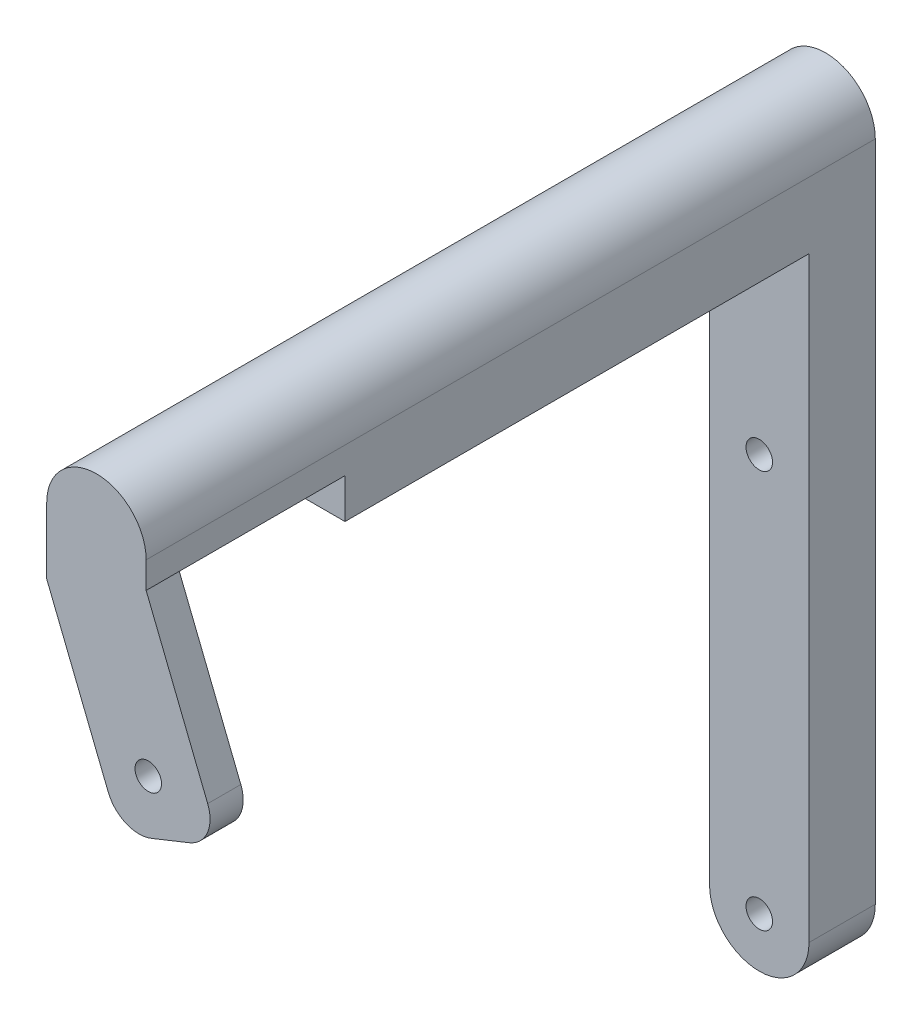
SolidWorks part; units mm, degrees
ref_plane "Plan de face" through (0, 0, 0) normal (0, 0, 1) x (1, 0, 0)
ref_plane "Plan de dessus" through (0, 0, 0) normal (0, 1, 0) x (1, 0, 0)
ref_plane "Plan de droite" through (0, 0, 0) normal (1, 0, 0) x (0, 0, -1)
sketch "Esquisse1" plane through (0, 0, 0) normal (0, 0, 1) x (1, 0, 0)
  line L0 (-15, 0) -> (-15, -200)
  line L1 (15, 0) -> (15, -200)
  circle A0 centre (0, 0) radius 4
  circle A1 centre (0, 0) radius 15
  circle A2 centre (0, -200) radius 15
  circle A4 centre (0, -80) radius 15
  circle A5 centre (0, -80) radius 4
  circle A6 centre (0, -200) radius 4
  dimension "D1" = 8
  dimension "D2" = 30
  dimension "D3" = 200
  dimension "D4" = 80
extrude "Boss.-Extru.1" add sketch "Esquisse1" along normal blind 20 contours A1 A0 | A4 A5 | A4 L1 A1 L0 | A4 L0 A2 L1 | A2 A6
sketch "Esquisse2" plane through (0, 0, 20) normal (0, 0, 1) x (1, 0, 0)
  line L0 (15, 0) -> (15, -200) construction
  line L2 (-15, 0) -> (-15, -20)
  line L3 (-15, -20) -> (15, -20)
  line L4 (15, 0) -> (15, -20)
  arc A0 (15, 0) -> (-15, 0) centre (0, 0) ccw construction
  arc A1 (15, 0) -> (-15, 0) centre (0, 0) ccw
  dimension "D1" = 20
extrude "Boss.-Extru.2" add sketch "Esquisse2" along normal blind 200
sketch "Esquisse5" plane through (0, 0, 220) normal (0, 0, 1) x (1, 0, 0)
  line L0 (-15, -20) -> (15, -8)
  line L1 (15, -20) -> (15, 0) construction
  line L2 (15, -8) -> (15, -20)
  line L3 (-15, -20) -> (15, -20) construction
  line L4 (-15, -20) -> (15, -20)
  dimension "D1" = 12
extrude "Enlèv. mat.-Extru.2" cut sketch "Esquisse5" against normal blind 60
sketch "Esquisse3" plane through (-1.0728, -14.4291, 0) normal (0.3714, -0.9285, 0) x (0.9285, 0.3714, 0)
  line L1 (-15, 220) -> (17.311, 220)
  line L2 (-15, 220) -> (-15, 210)
  line L3 (-15, 210) -> (17.311, 210)
  line L4 (17.311, 220) -> (17.311, 210)
  line L5 (17.311, 160) -> (17.311, 220) construction
  line L6 (17.311, 220) -> (-15, 220) construction
  dimension "D1" = 10
extrude "Boss.-Extru.3" add sketch "Esquisse3" along normal blind 60
fillet "Congé2" radius 10 2 edges at (37.2834, -63.7086, 215) (7.2834, -75.7086, 215)
sketch "Esquisse4" plane through (0, 0, 220) normal (0, 0, 1) x (1, 0, 0)
  line L0 (27.9987, -67.4225) -> (16.5682, -71.9947) construction
  line L2 (3.5695, -66.4238) -> (-15, -20) construction
  circle A0 centre (15.6397, -56.2106) radius 4
  dimension "D1" = 8
  dimension "D2" = 15
  dimension "D3" = 15
extrude "Enlèv. mat.-Extru.1" cut sketch "Esquisse4" against normal up to next
